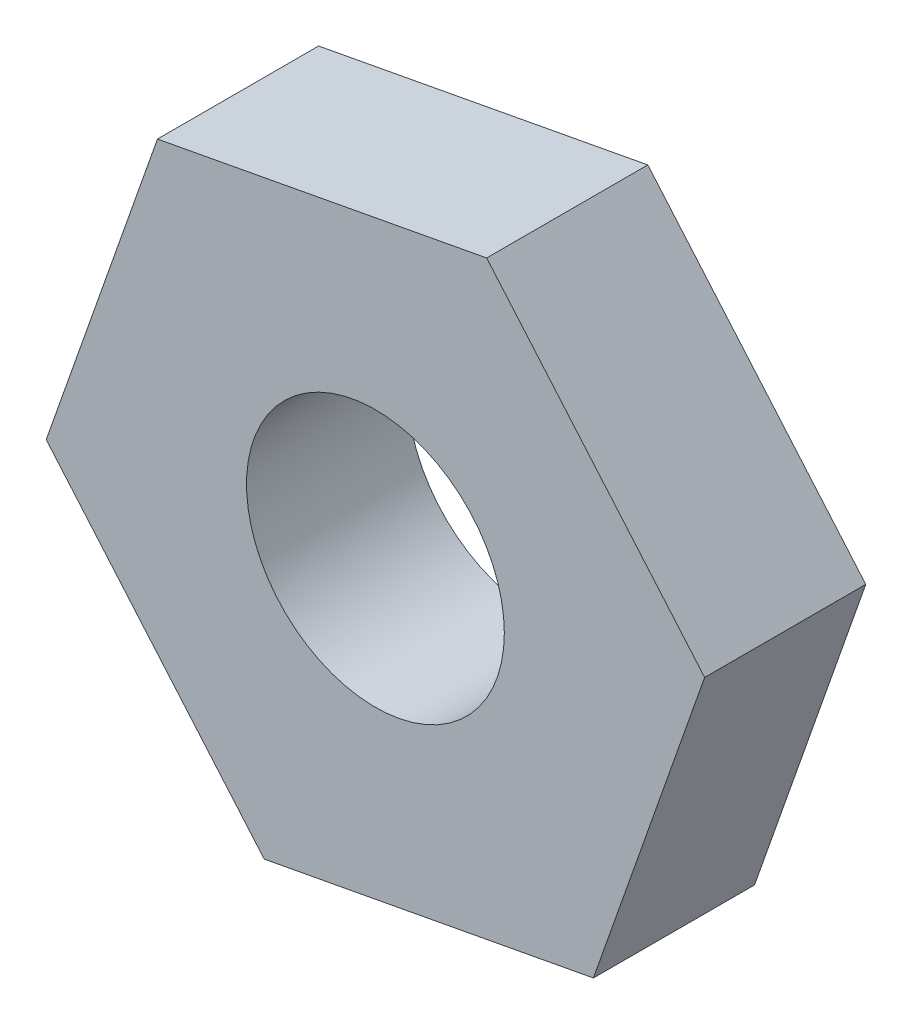
SolidWorks part; units mm, degrees
material "AISI 304"
ref_plane "Front Plane" through (0, 0, 0) normal (0, 0, 1) x (1, 0, 0)
ref_plane "Top Plane" through (0, 0, 0) normal (0, 1, 0) x (1, 0, 0)
ref_plane "Right Plane" through (0, 0, 0) normal (1, 0, 0) x (0, 0, -1)
sketch "Sketch1" plane through (0, 0, 0) normal (0, 0, 1) x (1, 0, 0)
  line L1 (6.7632, -7.8904) -> (10.2149, 1.9119)
  line L2 (10.2149, 1.9119) -> (3.4517, 9.8023)
  line L3 (3.4517, 9.8023) -> (-6.7632, 7.8904)
  line L4 (-6.7632, 7.8904) -> (-10.2149, -1.9119)
  line L5 (-10.2149, -1.9119) -> (-3.4517, -9.8023)
  line L6 (-3.4517, -9.8023) -> (6.7632, -7.8904)
  circle A0 centre (0, 0) radius 9 construction
  circle A1 centre (0, 0) radius 4
  dimension "D1" = 18
  dimension "D2" = 8
extrude "Boss-Extrude1" add sketch "Sketch1" along normal mid plane 5
